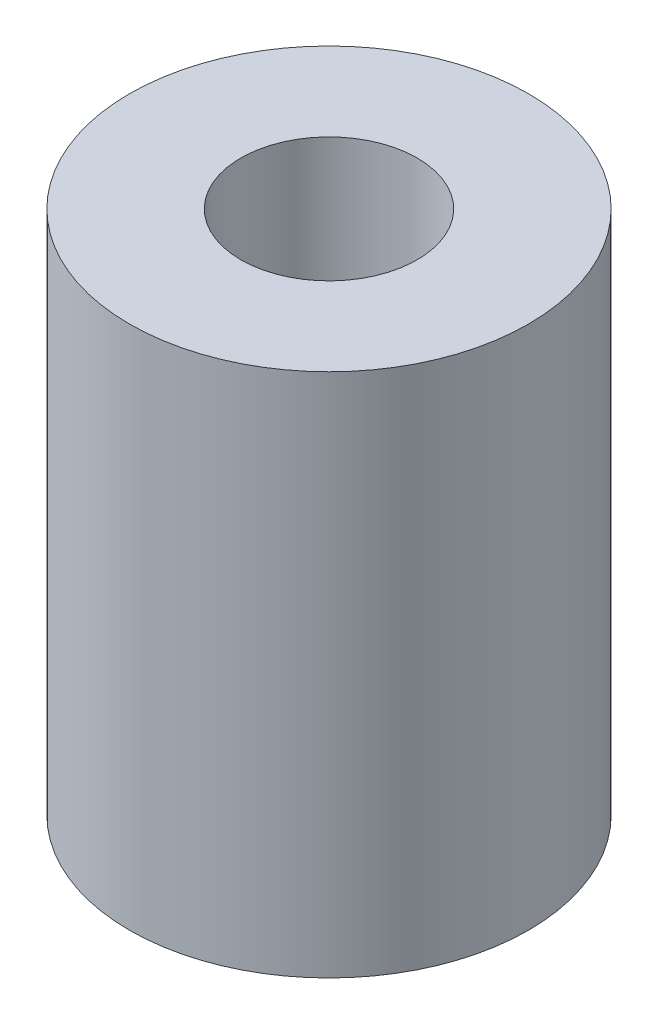
SolidWorks part; units mm, degrees
ref_plane "Front Plane" through (0, 0, 0) normal (0, 0, 1) x (1, 0, 0)
ref_plane "Top Plane" through (0, 0, 0) normal (0, 1, 0) x (1, 0, 0)
ref_plane "Right Plane" through (0, 0, 0) normal (1, 0, 0) x (0, 0, -1)
sketch "Sketch1" plane through (0, 0, 0) normal (0, 1, 0) x (1, 0, 0)
  circle A0 centre (0, 0) radius 9.5
  circle A1 centre (0, 0) radius 3.2
extrude "Boss-Extrude1" add sketch "Sketch1" along normal blind 25
sketch "Sketch2" plane through (0, 25, 0) normal (0, 1, 0) x (1, 0, 0)
  circle A0 centre (0, 0) radius 4.2
extrude "Cut-Extrude1" cut sketch "Sketch2" against normal blind 12.5
